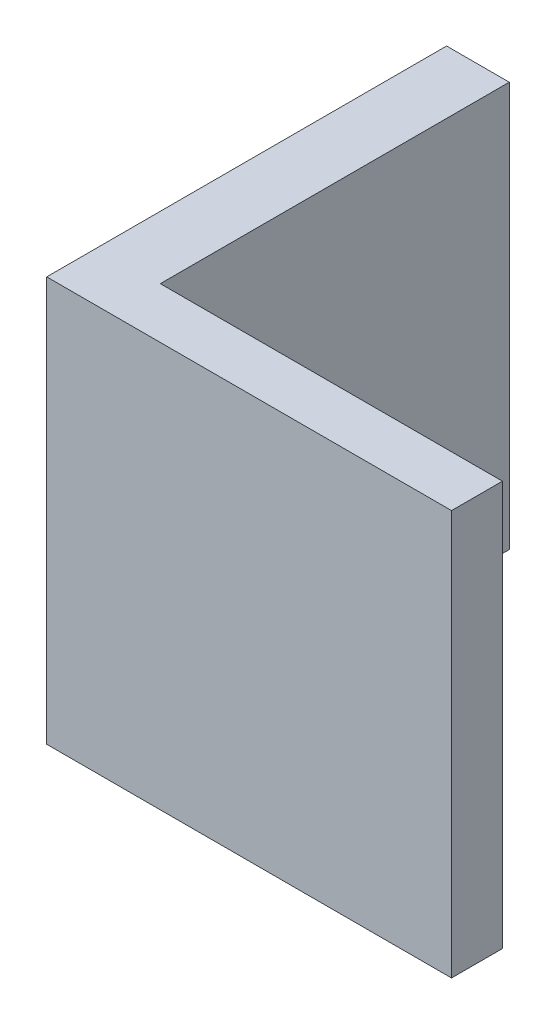
SolidWorks part; units mm, degrees
ref_plane "Front Plane" through (0, 0, 0) normal (0, 0, 1) x (1, 0, 0)
ref_plane "Top Plane" through (0, 0, 0) normal (0, 1, 0) x (1, 0, 0)
ref_plane "Right Plane" through (0, 0, 0) normal (1, 0, 0) x (0, 0, -1)
sketch "Sketch1" plane through (0, 0, 0) normal (0, 1, 0) x (1, 0, 0)
  line L1 (-75.1452, 27.258) -> (-64.9854, 27.258)
  line L2 (-75.1452, 27.258) -> (-75.1452, 17.2221)
  line L3 (-75.1452, 17.2221) -> (-64.9854, 17.2221)
  line L4 (-64.9854, 27.258) -> (-64.9854, 17.2221)
extrude "Boss-Extrude1" add sketch "Sketch1" along normal blind 10.16
sketch "Sketch2" plane through (0, 10.16, 0) normal (0, 1, 0) x (1, 0, 0)
  line L0 (-64.9854, 27.258) -> (-75.1452, 27.258) construction
  line L1 (-73.5718, 27.258) -> (-64.9854, 27.258)
  line L2 (-73.5718, 27.258) -> (-73.5718, 18.4997)
  line L3 (-73.5718, 18.4997) -> (-64.9854, 18.4997)
  line L4 (-64.9854, 27.258) -> (-64.9854, 18.4997)
  line L5 (-64.9854, 17.2221) -> (-64.9854, 27.258) construction
extrude "Cut-Extrude1" cut sketch "Sketch2" against normal blind 10.16
